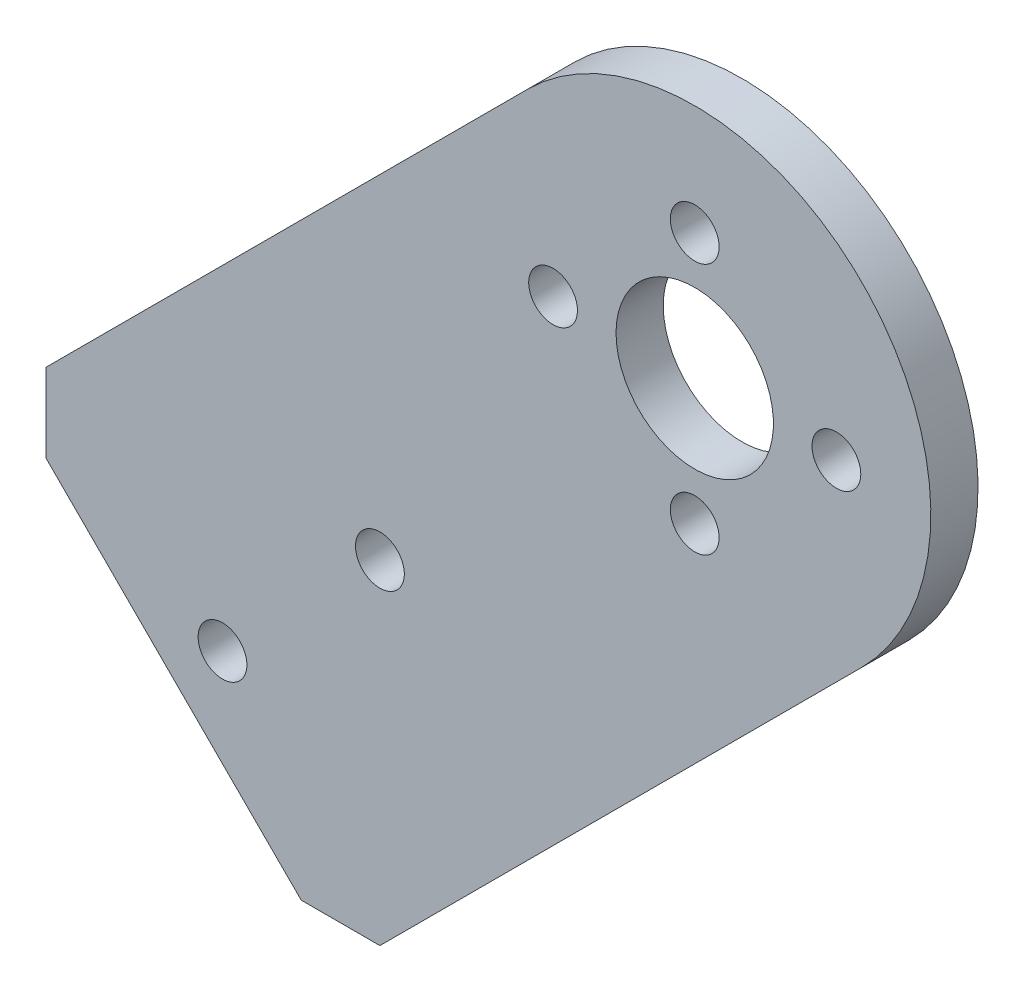
SolidWorks part; units mm, degrees
ref_plane "前基準面" through (0, 0, 0) normal (0, 0, 1) x (1, 0, 0)
ref_plane "上基準面" through (0, 0, 0) normal (0, 1, 0) x (1, 0, 0)
ref_plane "右基準面" through (0, 0, 0) normal (1, 0, 0) x (0, 0, -1)
sketch "草圖1" plane through (0, 0, 0) normal (0, 0, 1) x (1, 0, 0)
  line L1 (-70, -70) -> (70, -70)
  line L2 (-70, -70) -> (-70, 70)
  line L3 (-70, 70) -> (70, 70)
  line L4 (70, -70) -> (70, 70)
  line L5 (-70, -70) -> (70, 70) construction
  line L6 (-70, 70) -> (70, -70) construction
  line L7 (-60, -60) -> (60, -60) construction
  line L8 (-60, -60) -> (-60, 60) construction
  line L9 (-60, 60) -> (60, 60) construction
  line L10 (60, -60) -> (60, 60) construction
  line L11 (-60, -60) -> (60, 60) construction
  line L12 (-60, 60) -> (60, -60) construction
  circle A0 centre (-60, 60) radius 1.55
  circle A1 centre (60, 60) radius 1.55
  circle A2 centre (60, -60) radius 1.55
  circle A3 centre (-60, -60) radius 1.55
  point P0 (0, 0)
  point P6 (0, 0)
  dimension "D4" = 3.1
  dimension "D1" = 140
  dimension "D2" = 140
  dimension "D3" = 120
extrude "填料-伸長1" add sketch "草圖1" along normal blind 3
sketch "草圖2" plane through (0, 0, 3) normal (0, 0, 1) x (1, 0, 0)
  line L0 (-77.2505, 0) -> (82.0338, 0) construction
  line L1 (-55, 50) -> (-25, 50) construction
  line L2 (-55, 50) -> (-55, -50) construction
  line L3 (-55, -50) -> (-25, -50) construction
  line L4 (-25, 50) -> (-25, -50) construction
  line L5 (-55, 50) -> (-25, -50) construction
  line L6 (-55, -50) -> (-25, 50) construction
  line L7 (0, 57.5194) -> (0, -63.4985) construction
  line L8 (-40, 57.5194) -> (-40, -63.4985) construction
  line L9 (-60, 51.7794) -> (-60, -56.0844) construction
  line L10 (-58.5, -17.5) -> (-61.5, -17.5)
  line L11 (-58.5, 17.5) -> (-61.5, 17.5)
  line L12 (-58.5, 17.5) -> (-58.5, 42.5)
  line L13 (-58.5, 42.5) -> (-61.5, 42.5)
  line L14 (-61.5, 17.5) -> (-61.5, 42.5)
  line L15 (-58.5, 17.5) -> (-61.5, 42.5) construction
  line L16 (-58.5, 42.5) -> (-61.5, 17.5) construction
  line L17 (-61.5, -17.5) -> (-61.5, -42.5)
  line L18 (-58.5, -17.5) -> (-58.5, -42.5)
  line L19 (-58.5, -42.5) -> (-61.5, -42.5)
  line L20 (-21.5, -17.5) -> (-18.5, -17.5)
  line L21 (-21.5, -42.5) -> (-18.5, -42.5)
  line L22 (-21.5, -17.5) -> (-21.5, -42.5)
  line L23 (-18.5, -17.5) -> (-18.5, -42.5)
  line L24 (-21.5, 42.5) -> (-18.5, 42.5)
  line L25 (-21.5, 17.5) -> (-18.5, 17.5)
  line L26 (-21.5, 17.5) -> (-21.5, 42.5)
  line L27 (-18.5, 17.5) -> (-18.5, 42.5)
  line L28 (21.5, 42.5) -> (18.5, 42.5)
  line L29 (21.5, 17.5) -> (18.5, 17.5)
  line L30 (21.5, 17.5) -> (21.5, 42.5)
  line L31 (18.5, 17.5) -> (18.5, 42.5)
  line L32 (21.5, -42.5) -> (18.5, -42.5)
  line L33 (18.5, -17.5) -> (18.5, -42.5)
  line L34 (21.5, -17.5) -> (18.5, -17.5)
  line L35 (21.5, -17.5) -> (21.5, -42.5)
  line L36 (58.5, -42.5) -> (61.5, -42.5)
  line L37 (58.5, -17.5) -> (61.5, -17.5)
  line L38 (61.5, -17.5) -> (61.5, -42.5)
  line L39 (58.5, -17.5) -> (58.5, -42.5)
  line L40 (58.5, 42.5) -> (61.5, 42.5)
  line L41 (58.5, 17.5) -> (61.5, 17.5)
  line L42 (58.5, 17.5) -> (58.5, 42.5)
  line L43 (61.5, 17.5) -> (61.5, 42.5)
  line L45 (-12.25, 62.5) -> (12.25, 62.5) construction
  line L46 (-12.25, 62.5) -> (-12.25, 7.5) construction
  line L47 (-12.25, 7.5) -> (12.25, 7.5) construction
  line L48 (12.25, 62.5) -> (12.25, 7.5) construction
  line L49 (-12.25, 62.5) -> (12.25, 7.5) construction
  line L50 (-12.25, 7.5) -> (12.25, 62.5) construction
  circle A0 centre (-12.25, 62.5) radius 1.55
  circle A1 centre (12.25, 62.5) radius 1.55
  circle A2 centre (-12.25, 7.5) radius 1.55
  circle A3 centre (12.25, 7.5) radius 1.55
  point P0 (-40, 0)
  point P14 (-60, 30)
  point P47 (0, 35)
  dimension "D11" = 3.1
  dimension "D1" = 30
  dimension "D2" = 100
  dimension "D3" = 40
  dimension "D4" = 5
  dimension "D5" = 30
  dimension "D6" = 25
  dimension "D7" = 3
  dimension "D8" = 24.5
  dimension "D9" = 55
  dimension "D10" = 35
extrude "除料-伸長1" cut sketch "草圖2" against normal through all
sketch "草圖3" plane through (0, 0, 3) normal (0, 0, 1) x (1, 0, 0)
  line L0 (-79.3934, 100.6066) -> (-48.7868, 70)
  line L1 (-90, -90) -> (90, -90) construction
  line L2 (-90, -90) -> (-90, 90) construction
  line L3 (-90, 90) -> (90, 90) construction
  line L4 (90, -90) -> (90, 90) construction
  line L5 (-90, -90) -> (90, 90) construction
  line L6 (-90, 90) -> (90, -90) construction
  line L7 (70, 70) -> (-70, 70) construction
  line L8 (-100.6066, 79.3934) -> (-70, 48.7868)
  line L9 (-48.7868, 70) -> (-70, 70)
  line L10 (-70, 70) -> (-70, 48.7868)
  line L11 (0, 103.8199) -> (0, 0) construction
  line L12 (0, 0) -> (-105.1877, 0) construction
  line L13 (48.7868, 70) -> (70, 70)
  line L14 (70, 70) -> (70, 48.7868)
  line L15 (100.6066, 79.3934) -> (70, 48.7868)
  line L16 (79.3934, 100.6066) -> (48.7868, 70)
  line L17 (-48.7868, -70) -> (-70, -70)
  line L18 (-70, -70) -> (-70, -48.7868)
  line L19 (-100.6066, -79.3934) -> (-70, -48.7868)
  line L20 (-79.3934, -100.6066) -> (-48.7868, -70)
  line L21 (79.3934, -100.6066) -> (48.7868, -70)
  line L22 (48.7868, -70) -> (70, -70)
  line L23 (70, -70) -> (70, -48.7868)
  line L24 (100.6066, -79.3934) -> (70, -48.7868)
  circle A0 centre (-90, 90) radius 5
  circle A1 centre (-81, 90) radius 1.55
  circle A2 centre (-90, 98) radius 1.55
  circle A3 centre (-99, 90) radius 1.55
  circle A4 centre (-90, 82) radius 1.55
  arc A5 (-79.3934, 100.6066) -> (-100.6066, 79.3934) centre (-90, 90) ccw
  circle A6 centre (81, 90) radius 1.55
  circle A7 centre (90, 90) radius 5
  circle A8 centre (90, 82) radius 1.55
  circle A9 centre (90, 98) radius 1.55
  circle A10 centre (99, 90) radius 1.55
  arc A11 (79.3934, 100.6066) -> (100.6066, 79.3934) centre (90, 90) cw
  circle A12 centre (-90, -82) radius 1.55
  circle A13 centre (-90, -90) radius 5
  circle A14 centre (-81, -90) radius 1.55
  circle A15 centre (-90, -98) radius 1.55
  circle A16 centre (-99, -90) radius 1.55
  arc A17 (-79.3934, -100.6066) -> (-100.6066, -79.3934) centre (-90, -90) cw
  circle A18 centre (90, -82) radius 1.55
  circle A19 centre (90, -90) radius 5
  circle A20 centre (81, -90) radius 1.55
  circle A21 centre (90, -98) radius 1.55
  circle A22 centre (99, -90) radius 1.55
  arc A23 (79.3934, -100.6066) -> (100.6066, -79.3934) centre (90, -90) ccw
  point P0 (0, 0)
  dimension "D3" = 10
  dimension "D4" = 3.1
  dimension "D5" = 3.1
  dimension "D7" = 9
  dimension "D8" = 30
  dimension "D1" = 180
  dimension "D2" = 180
  dimension "D6" = 8
extrude "填料-伸長2" add sketch "草圖3" against normal blind 3
sketch "草圖4" plane through (0, 0, 0) normal (0, 0, -1) x (-1, 0, 0)
  line L0 (-70, 48.7868) -> (-65, 48.7868)
  line L5 (-70, -48.7868) -> (-70, 48.7868) construction
  line L6 (-100.6066, -79.3934) -> (-70, -48.7868) construction
  line L7 (-65, 48.7868) -> (-48.7868, 65)
  line L8 (-48.7868, 65) -> (-48.7868, 70)
  line L9 (-70, 70) -> (-60, 60) construction
  line L10 (48.7868, -70) -> (-48.7868, -70) construction
  line L11 (-48.7868, -70) -> (-79.3934, -100.6066) construction
  line L12 (79.3934, -100.6066) -> (48.7868, -70) construction
  line L13 (70, -48.7868) -> (100.6066, -79.3934) construction
  line L14 (70, 48.7868) -> (70, -48.7868) construction
  line L15 (100.6066, 79.3934) -> (70, 48.7868) construction
  line L16 (48.7868, 70) -> (79.3934, 100.6066) construction
  line L17 (-48.7868, 70) -> (48.7868, 70) construction
  line L18 (-70, -48.7868) -> (-70, 48.7868)
  line L19 (-100.6066, -79.3934) -> (-70, -48.7868)
  line L20 (48.7868, -70) -> (-48.7868, -70)
  line L21 (-48.7868, -70) -> (-79.3934, -100.6066)
  line L22 (79.3934, -100.6066) -> (48.7868, -70)
  line L23 (70, -48.7868) -> (100.6066, -79.3934)
  line L24 (70, 48.7868) -> (70, -48.7868)
  line L25 (100.6066, 79.3934) -> (70, 48.7868)
  line L26 (48.7868, 70) -> (79.3934, 100.6066)
  line L27 (-48.7868, 70) -> (48.7868, 70)
  circle A0 centre (-70, 70) radius 1.55
  circle A3 centre (-60, 60) radius 1.55 construction
  arc A4 (-100.6066, -79.3934) -> (-79.3934, -100.6066) centre (-90, -90) ccw construction
  arc A5 (79.3934, -100.6066) -> (100.6066, -79.3934) centre (90, -90) ccw construction
  arc A6 (100.6066, 79.3934) -> (79.3934, 100.6066) centre (90, 90) ccw construction
  arc A7 (-100.6066, -79.3934) -> (-79.3934, -100.6066) centre (-90, -90) ccw
  arc A8 (79.3934, -100.6066) -> (100.6066, -79.3934) centre (90, -90) ccw
  arc A9 (100.6066, 79.3934) -> (79.3934, 100.6066) centre (90, 90) ccw
  point P0 (0, 0)
  dimension "D3" = 3.1
  dimension "D4" = 14.1421
  dimension "D1" = 5
  dimension "D2" = 5
extrude "除料-伸長2" cut sketch "草圖4" against normal blind 10
